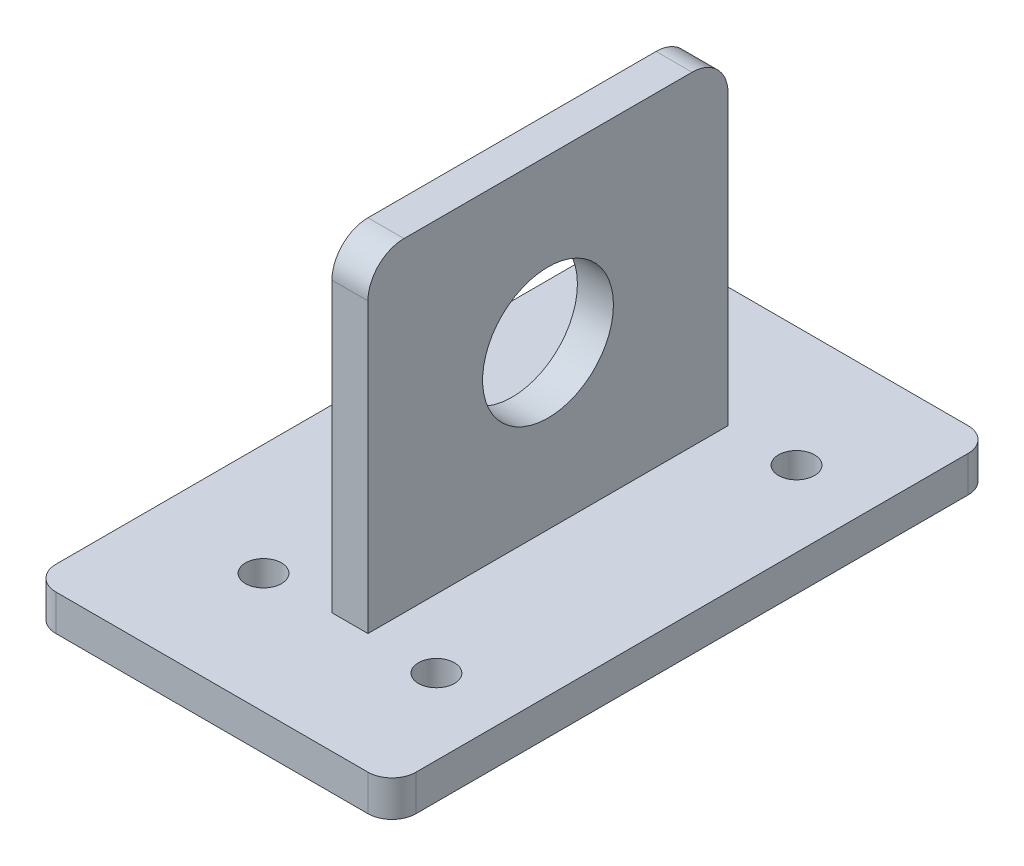
SolidWorks part; units mm, degrees
ref_plane "前视基准面" through (0, 0, 0) normal (0, 0, 1) x (1, 0, 0)
ref_plane "上视基准面" through (0, 0, 0) normal (0, 1, 0) x (1, 0, 0)
ref_plane "右视基准面" through (0, 0, 0) normal (1, 0, 0) x (0, 0, -1)
sketch "草图1" plane through (0, 0, 0) normal (0, 1, 0) x (1, 0, 0)
  line L1 (15, -25) -> (-15, -25)
  line L2 (15, -25) -> (15, 25)
  line L3 (15, 25) -> (-15, 25)
  line L4 (-15, -25) -> (-15, 25)
  line L5 (15, -25) -> (-15, 25) construction
  line L6 (15, 25) -> (-15, -25) construction
  point P0 (0, 0)
extrude "凸台-拉伸1" add sketch "草图1" along normal blind 3
sketch "草图2" plane through (0, 0, 0) normal (1, 0, 0) x (0, 0, -1)
  line L0 (0, 0) -> (0, 29.4133) construction
  line L1 (0, 0) -> (15, 0) construction
  line L3 (15, 0) -> (-15, 0)
  line L4 (15, 0) -> (15, 30)
  line L5 (15, 30) -> (-15, 30)
  line L6 (-15, 0) -> (-15, 30)
extrude "凸台-拉伸2" add sketch "草图2" along normal blind 3
sketch "草图3" plane through (3, 0, 0) normal (1, 0, 0) x (0, 0, -1)
  circle A0 centre (0, 16.5) radius 5.45
extrude "切除-拉伸1" cut sketch "草图3" against normal blind 3
fillet "圆角1" radius 2 4 edges at (15, 1.5, 25) (-15, 1.5, 25) (15, 1.5, -25) (-15, 1.5, -25)
fillet "圆角2" radius 3 2 edges at (1.5, 30, 15) (1.5, 30, -15)
sketch "草图4" plane through (0, 3, 0) normal (0, 1, 0) x (1, 0, 0)
  circle A0 centre (-5.7035, 15) radius 1.5
extrude "切除-拉伸2" cut sketch "草图4" against normal blind 3
mirror "镜向1" about plane through (0, 0, 0) normal (0, 0, 1) of "切除-拉伸2"
ref_plane "基准面1" through (1.5, 0, 0) normal (1, 0, 0) x (0, 0, -1)
mirror "镜向2" about plane through (1.5, 0, 0) normal (1, 0, 0) of "镜向1", "切除-拉伸2"
